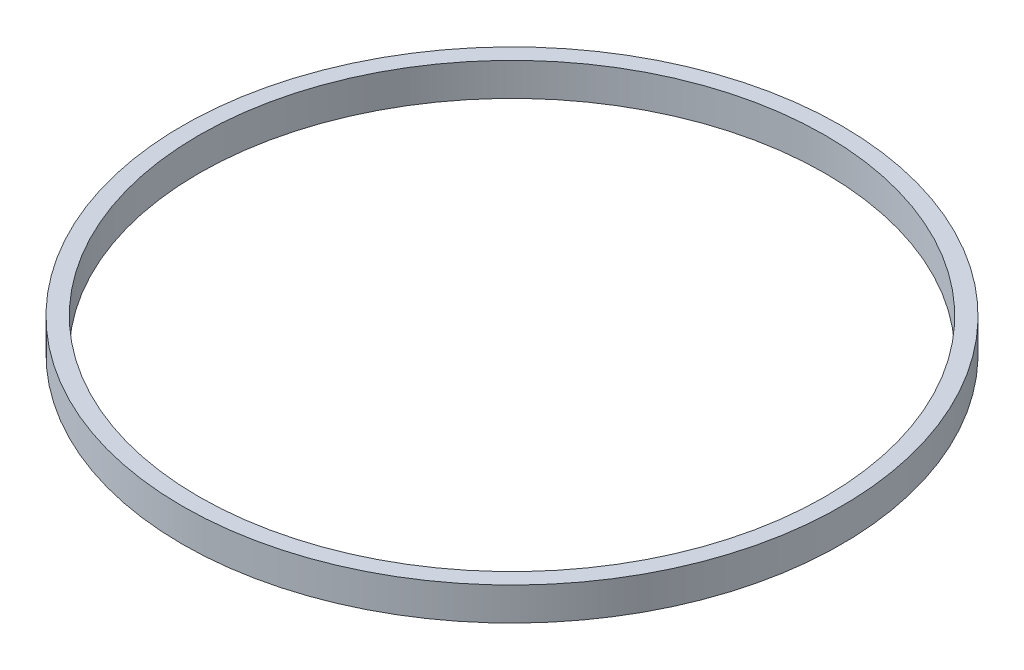
SolidWorks part; units mm, degrees
ref_plane "Front Plane" through (0, 0, 0) normal (0, 0, 1) x (1, 0, 0)
ref_plane "Top Plane" through (0, 0, 0) normal (0, 1, 0) x (1, 0, 0)
ref_plane "Right Plane" through (0, 0, 0) normal (1, 0, 0) x (0, 0, -1)
sketch "Sketch1" plane through (0, 0, 0) normal (0, 1, 0) x (1, 0, 0)
  circle A0 centre (0, 0) radius 25.4
  circle A1 centre (0, 0) radius 24.13
  dimension "D1" = 50.8
  dimension "D2" = 48.26
extrude "Boss-Extrude1" add sketch "Sketch1" along normal blind 2.54
